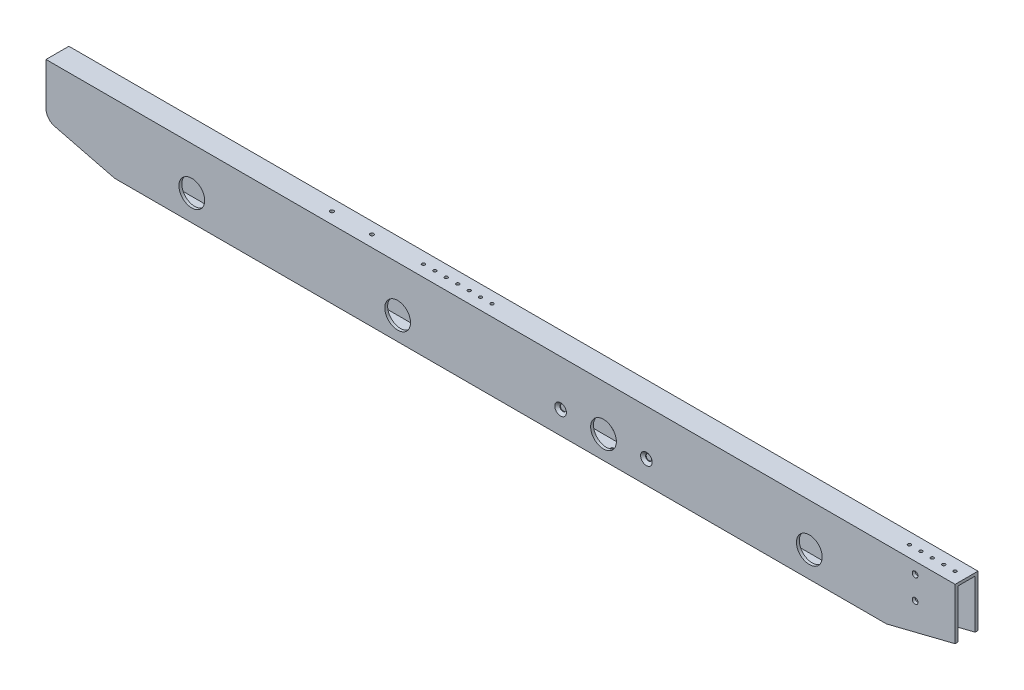
SolidWorks part; units mm, degrees
material "6061-T6 (SS)"
ref_plane "Front Plane" through (0, 0, 0) normal (0, 0, 1) x (1, 0, 0)
ref_plane "Top Plane" through (0, 0, 0) normal (0, 1, 0) x (1, 0, 0)
ref_plane "Right Plane" through (0, 0, 0) normal (1, 0, 0) x (0, 0, -1)
sketch "Sketch1" plane through (0, 0, 0) normal (0, 0, 1) x (1, 0, 0)
  line L0 (0, -12.7) -> (-342.9, -9.525) construction
  line L1 (-504.825, 38.1) -> (504.825, 38.1)
  line L2 (-504.825, 38.1) -> (-504.825, -38.1)
  line L3 (-504.825, -38.1) -> (504.825, -38.1)
  line L4 (504.825, 38.1) -> (504.825, -38.1)
  line L5 (-504.825, 38.1) -> (504.825, -38.1) construction
  line L6 (-504.825, -38.1) -> (504.825, 38.1) construction
  line L7 (-504.825, -38.1) -> (504.825, -38.1) construction
  line L8 (-504.825, -38.1) -> (-504.825, 12.7) construction
  line L9 (-339.7523, -73.025) -> (358.7477, -73.025) construction
  line L10 (-504.825, 12.7) -> (504.825, 12.7) construction
  line L11 (504.825, -38.1) -> (504.825, 12.7) construction
  line L12 (0, -12.7) -> (342.9, -9.525) construction
  line L13 (-114.3, -12.7) -> (114.3, -12.7) construction
  circle A0 centre (-114.3, -12.7) radius 14.2875
  circle A1 centre (114.3, -12.7) radius 14.2875
  circle A2 centre (-342.9, -9.525) radius 14.2875
  circle A3 centre (342.9, -9.525) radius 14.2875
  circle A4 centre (-342.9, -9.525) radius 63.5 construction
  circle A5 centre (-114.3, -12.7) radius 63.5 construction
  circle A6 centre (114.3, -12.7) radius 63.5 construction
  circle A7 centre (342.9, -9.525) radius 63.5 construction
  point P0 (0, 0)
  point P12 (0, -38.1)
  dimension "D5" = 228.6
  dimension "D4" = 50.8
  dimension "D8" = 228.6
  dimension "D9" = 28.575
  dimension "D6" = 28.575
  dimension "D10" = 127
  dimension "D1" = 76.2
  dimension "D2" = 1009.65
  dimension "D3" = 25.4
  dimension "D7" = 228.6
extrude "Boss-Extrude2" add sketch "Sketch1" along normal mid plane 25.4
sketch "Sketch3" plane through (504.825, 0, 0) normal (1, 0, 0) x (0, 0, -1)
  line L8 (9.525, -34.925) -> (9.525, 34.925)
  line L9 (9.525, 34.925) -> (-9.525, 34.925)
  line L10 (-9.525, 34.925) -> (-9.525, -34.925)
  line L11 (-9.525, -34.925) -> (9.525, -34.925)
  line L12 (9.525, -34.925) -> (9.525, 34.925)
  line L13 (9.525, 34.925) -> (-9.525, 34.925)
  line L14 (-9.525, 34.925) -> (-9.525, -34.925)
  line L15 (-9.525, -34.925) -> (9.525, -34.925)
  dimension "D1" = 3.175
extrude "Cut-Extrude2" cut sketch "Sketch3" against normal through all
sketch "Sketch4" plane through (0, 0, 12.7) normal (0, 0, 1) x (1, 0, 0)
  line L0 (-504.825, -38.1) -> (-504.825, -19.05)
  line L1 (-504.825, 38.1) -> (-504.825, -38.1) construction
  line L2 (-504.825, -19.05) -> (-428.625, -38.1)
  line L3 (-504.825, -38.1) -> (504.825, -38.1) construction
  line L4 (-428.625, -38.1) -> (-504.825, -38.1)
  line L5 (0, -38.1) -> (0, 38.1) construction
  line L6 (504.825, 38.1) -> (-504.825, 38.1) construction
  line L7 (428.625, -38.1) -> (504.825, -38.1)
  line L8 (504.825, -38.1) -> (504.825, -19.05)
  line L9 (504.825, -19.05) -> (428.625, -38.1)
  line L11 (504.825, -19.05) -> (504.825, 38.1) construction
  point P15 (0, 0)
  dimension "D1" = 19.05
  dimension "D2" = 57.15
  dimension "D3" = 76.2
  dimension "D4" = 504.825
  dimension "D5" = 14.036
extrude "Cut-Extrude3" cut sketch "Sketch4" against normal through all
fillet "Fillet1" radius 12.7 2 edges at (-504.825, -19.05, -11.1125) (-504.825, -19.05, 11.1125)
sketch "Sketch9" plane through (0, 38.1, 0) normal (0, 1, 0) x (1, 0, 0)
  line L0 (504.825, -12.7) -> (504.825, 12.7) construction
  circle A0 centre (492.125, 0) radius 1.7272
  circle A1 centre (479.425, 0) radius 1.7272
  circle A2 centre (466.725, 0) radius 1.7272
  circle A3 centre (454.025, 0) radius 1.7272
  circle A4 centre (441.325, 0) radius 1.7272
  point P2 (504.825, 0)
  dimension "D1" = 3.4544
  dimension "D2" = 12.7
  dimension "D3" = 4
  dimension "D4" = 2
extrude "Cut-Extrude4" cut sketch "Sketch9" against normal blind 2.54
sketch "Sketch12" plane through (0, 38.1, 0) normal (0, 1, 0) x (1, 0, 0)
  line L0 (-504.825, -12.7) -> (-504.825, 12.7) construction
  circle A0 centre (-98.425, 0) radius 1.7272
  circle A1 centre (-85.725, 0) radius 1.7272
  circle A2 centre (-73.025, 0) radius 1.7272
  circle A3 centre (-60.325, 0) radius 1.7272
  circle A4 centre (-47.625, 0) radius 1.7272
  circle A5 centre (-34.925, 0) radius 1.7272
  circle A6 centre (-22.225, 0) radius 1.7272
  point P5 (-28.575, 0)
  point P15 (-504.825, 0)
  dimension "D1" = 3.4544
  dimension "D2" = 406.4
  dimension "D4" = 476.25
  dimension "D3" = 7
extrude "Cut-Extrude7" cut sketch "Sketch12" against normal blind 5.08
hole_wizard "CSK for 1/4 Flat Head Machine Screw (100)2" positions "Sketch16" profile "Sketch15" countersink size "1/4" standard "ANSI Inch" end condition through all
sketch "Sketch16" plane through (0, 0, 12.7) normal (0, 0, 1) x (1, 0, 0)
  circle A0 centre (114.3, -12.7) radius 14.2875 construction
  point P4 (66.675, -12.7)
  point P6 (161.925, -12.7)
  dimension "D1" = 47.625
  dimension "D2" = 47.625
sketch "Sketch15" plane through (66.675, -12.7, 12.7) normal (1, 0, 0) x (0, -1, 0)
  line L0 (0, 0) -> (0, 25.4)
  line L1 (0, 25.4) -> (3.3782, 25.4)
  line L2 (3.3782, 25.4) -> (3.3782, 2.5682)
  line L3 (3.3782, 2.5682) -> (6.4389, 0)
  line L5 (6.4389, 0) -> (0, 0)
  line L6 (-3.3782, 2.5682) -> (-6.4389, 0) construction
  line L11 (0, -6.35) -> (0, 107.95) construction
  dimension "Thru Hole Dia." = 6.7564
  dimension "Thru Hole Depth" = 25.4
  dimension "Near C'Sink Dia." = 12.8778
  dimension "Near C'Sink Angle" = 100
sketch "Sketch17" plane through (0, -38.1, 0) normal (0, -1, 0) x (-1, 0, 0)
  line L0 (-428.625, 12.7) -> (-428.625, -12.7) construction
  circle A0 centre (-415.925, 0) radius 1.7272
  circle A1 centre (-396.875, 0) radius 1.7272
  circle A2 centre (-377.825, 0) radius 1.7272
  circle A3 centre (-358.775, 0) radius 1.7272
  circle A4 centre (-339.725, 0) radius 1.7272
  circle A5 centre (-320.675, 0) radius 1.7272
  circle A6 centre (-301.625, 0) radius 1.7272
  circle A7 centre (-282.575, 0) radius 1.7272
  circle A8 centre (-263.525, 0) radius 1.7272
  circle A9 centre (-244.475, 0) radius 1.7272
  circle A10 centre (-225.425, 0) radius 1.7272
  circle A11 centre (-206.375, 0) radius 1.7272
  circle A12 centre (-187.325, 0) radius 1.7272
  circle A13 centre (-168.275, 0) radius 1.7272
  circle A14 centre (-149.225, 0) radius 1.7272
  circle A15 centre (-130.175, 0) radius 1.7272
  circle A16 centre (-111.125, 0) radius 1.7272
  circle A17 centre (-92.075, 0) radius 1.7272
  circle A18 centre (-73.025, 0) radius 1.7272
  circle A19 centre (-53.975, 0) radius 1.7272
  circle A20 centre (-34.925, 0) radius 1.7272
  circle A21 centre (-15.875, 0) radius 1.7272
  circle A22 centre (3.175, 0) radius 1.7272
  circle A23 centre (22.225, 0) radius 1.7272
  circle A24 centre (41.275, 0) radius 1.7272
  circle A25 centre (60.325, 0) radius 1.7272
  point P2 (-428.625, 0)
  dimension "D1" = 3.4544
  dimension "D2" = 12.7
  dimension "D3" = 26
extrude "Cut-Extrude8" cut sketch "Sketch17" against normal blind 6.35
sketch "Sketch18" plane through (0, 0, -12.7) normal (0, 0, -1) x (-1, 0, 0)
  circle A0 centre (-114.3, -12.7) radius 17.4625
  dimension "D1" = 34.925
extrude "Cut-Extrude9" cut sketch "Sketch18" against normal blind 3.81
hole_wizard "1/4 (0.25) Diameter Hole1" positions "Sketch20" profile "Sketch19" hole size "1/4" standard "ANSI Inch" end condition through all
sketch "Sketch20" plane through (0, 0, 12.7) normal (0, 0, 1) x (1, 0, 0)
  line L0 (504.825, -19.05) -> (504.825, 38.1) construction
  line L1 (504.825, 38.1) -> (-504.825, 38.1) construction
  point P0 (460.375, 25.4)
  point P2 (460.375, 0)
  dimension "D1" = 25.4
  dimension "D2" = 44.45
  dimension "D3" = 12.7
sketch "Sketch19" plane through (460.375, 25.4, 12.7) normal (1, 0, 0) x (0, -1, 0)
  line L0 (0, 0) -> (0, 25.4)
  line L1 (0, 25.4) -> (3.175, 25.4)
  line L2 (3.175, 25.4) -> (3.175, 0)
  line L5 (3.175, 0) -> (0, 0)
  line L11 (0, -6.35) -> (0, 107.95) construction
  dimension "Thru Hole Dia." = 6.35
  dimension "Thru Hole Depth" = 25.4
hole_wizard "#10-32 Tapped Hole1" positions "Sketch22" profile "Sketch21" tap size "#10-32" standard "ANSI Inch"
sketch "Sketch22" plane through (0, 38.1, 0) normal (0, 1, 0) x (1, 0, 0)
  circle A0 centre (-60.325, 0) radius 1.7272 construction
  point P0 (-155.575, 0)
  point P2 (-200.025, 0)
  dimension "D1" = 95.25
  dimension "D2" = 44.45
cosmetic thread "Hole Thread1" parameters "D1"=3.175, "D2"=4.826
cosmetic thread "Hole Thread2" parameters "D1"=3.175, "D2"=4.826
sketch "Sketch21" plane through (-155.575, 38.1, 0) normal (1, 0, 0) x (0, 0, 1)
  line L0 (0, 0) -> (0, 14.9293)
  line L1 (0, 14.9293) -> (2.0193, 13.716)
  line L2 (2.0193, 13.716) -> (2.0193, 0)
  line L5 (2.0193, 0) -> (0, 0)
  line L10 (0, 14.9293) -> (-2.0193, 13.716) construction
  line L11 (0, -6.35) -> (0, 107.95) construction
  dimension "Tap Drill Dia." = 4.0386
  dimension "Tap Drill Depth" = 13.716
  dimension "Drill Angle" = 118
